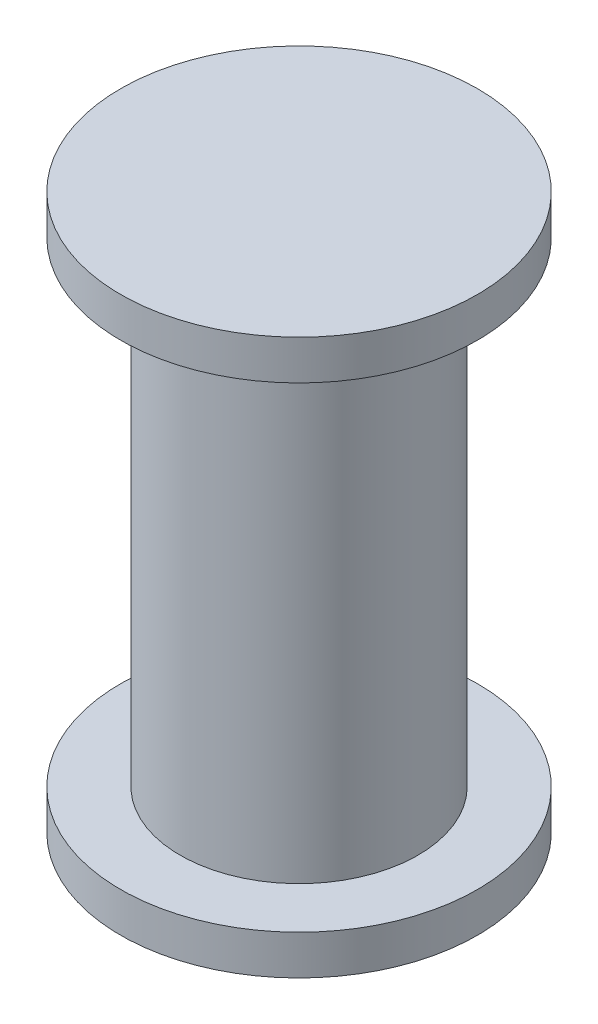
SolidWorks part; units mm, degrees
ref_plane "Front Plane" through (0, 0, 0) normal (0, 0, 1) x (1, 0, 0)
ref_plane "Top Plane" through (0, 0, 0) normal (0, 1, 0) x (1, 0, 0)
ref_plane "Right Plane" through (0, 0, 0) normal (1, 0, 0) x (0, 0, -1)
sketch "Sketch1" plane through (0, 0, 0) normal (0, 0, 1) x (1, 0, 0)
  line L0 (0, 0) -> (0, 14)
  line L1 (0, 14) -> (-4.5, 14)
  line L2 (-4.5, 14) -> (-4.5, 13)
  line L3 (-4.5, 13) -> (-3, 13)
  line L4 (-3, 13) -> (-3, 1)
  line L5 (-3, 1) -> (-4.5, 1)
  line L6 (-4.5, 1) -> (-4.5, 0)
  line L7 (-4.5, 0) -> (0, 0)
  dimension "D1" = 14
  dimension "D2" = 1
  dimension "D3" = 1
  dimension "D4" = 3
  dimension "D5" = 4.5
  dimension "D6" = 4.5
revolve "Revolve1" add sketch "Sketch1" angle 360 about L0
